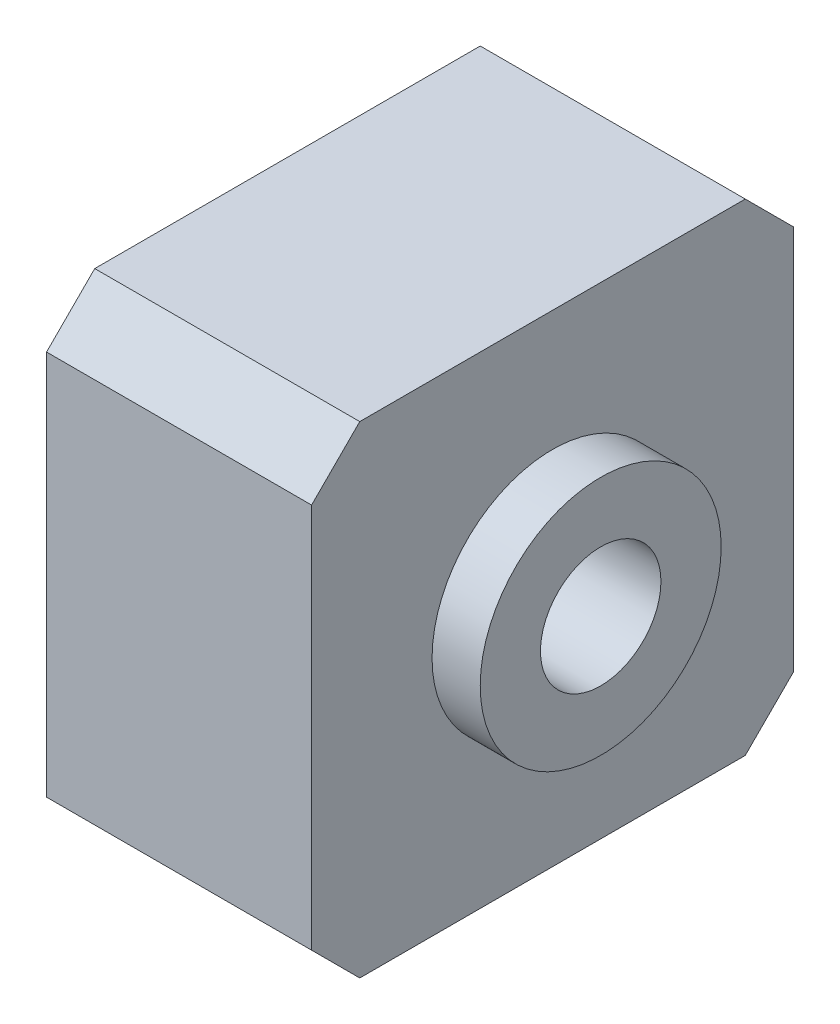
SolidWorks part; units mm, degrees
ref_plane "Front Plane" through (0, 0, 0) normal (0, 0, 1) x (1, 0, 0)
ref_plane "Top Plane" through (0, 0, 0) normal (0, 1, 0) x (1, 0, 0)
ref_plane "Right Plane" through (0, 0, 0) normal (1, 0, 0) x (0, 0, -1)
sketch "Sketch1" plane through (0, 0, 0) normal (1, 0, 0) x (0, 0, -1)
  line L1 (-10, -10) -> (10, -10)
  line L2 (10, -10) -> (10, 10)
  line L3 (10, 10) -> (-10, 10)
  line L4 (-10, 10) -> (-10, -10)
  circle A0 centre (0, 0) radius 10 construction
extrude "Boss-Extrude1" add sketch "Sketch1" against normal blind 17
sketch "Sketch2" plane through (0, 0, 0) normal (1, 0, 0) x (0, 0, -1)
  circle A0 centre (0, 0) radius 5
  circle A1 centre (0, 0) radius 15.3536
extrude "Cut-Extrude1" cut sketch "Sketch2" against normal blind 2
sketch "Sketch3" plane through (-17, 0, 0) normal (-1, 0, 0) x (0, 0, 1)
  circle A0 centre (0, 0) radius 5
  circle A1 centre (0, 0) radius 15.6354
extrude "Cut-Extrude2" cut sketch "Sketch3" against normal blind 4
sketch "Sketch4" plane through (0, 0, 0) normal (1, 0, 0) x (0, 0, -1)
  circle A0 centre (0, 0) radius 2.5
extrude "Cut-Extrude3" cut sketch "Sketch4" against normal through all
chamfer "Chamfer1" distance 2 angle 45 4 edges at (-7.5, -10, -10) (-7.5, -10, 10) (-7.5, 10, 10) (-7.5, 10, -10)
sketch "Sketch5" plane through (0, 0, -10) normal (0, 0, -1) x (-1, 0, 0)
  line L0 (0, 0) -> (7, 0) construction
  line L1 (0, 5) -> (0, -5) construction
  circle A0 centre (7, 0) radius 2.75
  dimension "D1" = 5.5
  dimension "D2" = 7
extrude "Cut-Extrude4" cut sketch "Sketch5" against normal blind 2
